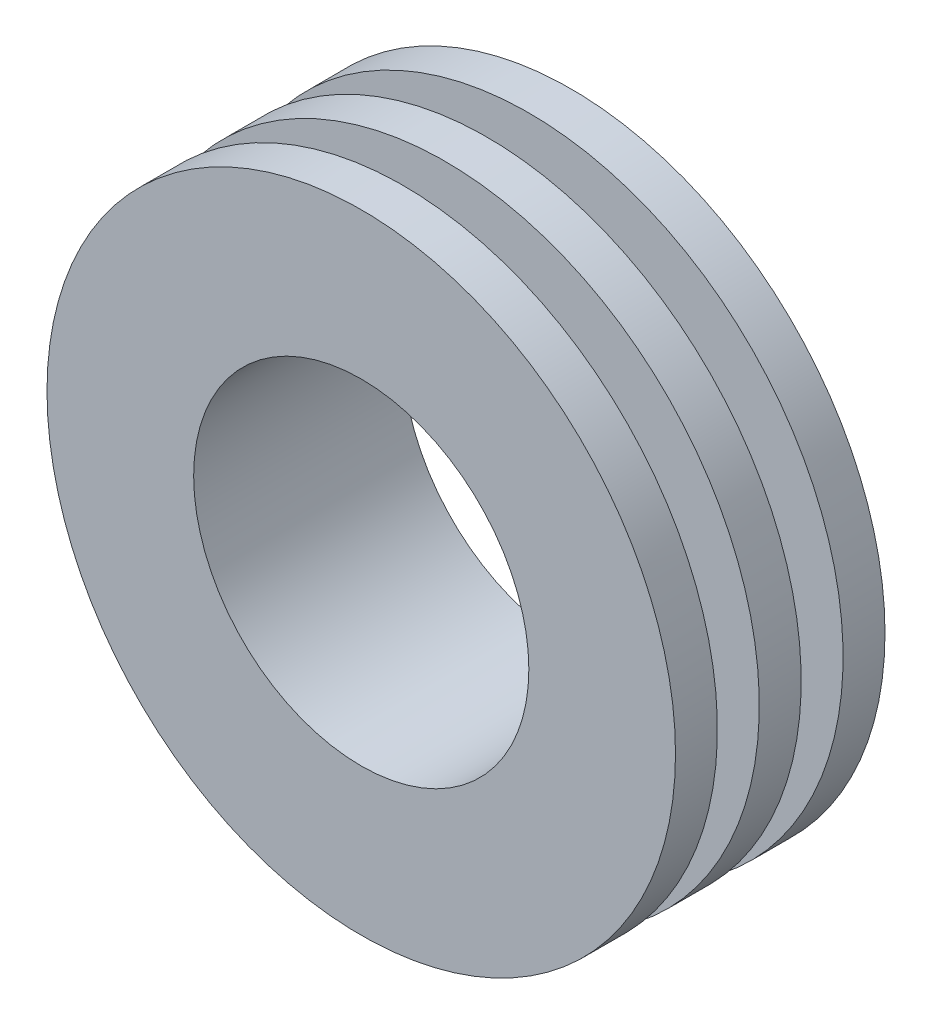
SolidWorks part; units mm, degrees
material "6061 合金"
ref_plane "前视基准面" through (0, 0, 0) normal (0, 0, 1) x (1, 0, 0)
ref_plane "上视基准面" through (0, 0, 0) normal (0, 1, 0) x (1, 0, 0)
ref_plane "右视基准面" through (0, 0, 0) normal (1, 0, 0) x (0, 0, -1)
sketch "草图1" plane through (0, 0, 0) normal (0, 0, 1) x (1, 0, 0)
  circle A0 centre (0, 0) radius 4
  circle A1 centre (0, 0) radius 7.5
  dimension "D1" = 8
  dimension "D2" = 15
extrude "凸台-拉伸1" add sketch "草图1" along normal blind 5
sketch "草图2" plane through (0, 0, 0) normal (1, 0, 0) x (0, 0, -1)
  line L0 (0, 0) -> (-5, 0) construction
  line L1 (-2.5, 0) -> (-2.5, 9.5205) construction
  line L2 (-5, 7.5) -> (-5, -7.5) construction
  line L3 (-4, 7.5) -> (-3, 7.5)
  line L4 (-4, 7.5) -> (-4, 6)
  line L5 (-4, 6) -> (-3, 6)
  line L6 (-3, 7.5) -> (-3, 6)
  line L7 (-2, 7.5) -> (-2, 6)
  line L8 (-1, 6) -> (-2, 6)
  line L9 (-1, 7.5) -> (-1, 6)
  line L10 (-1, 7.5) -> (-2, 7.5)
  dimension "D1" = 1
  dimension "D2" = 1
  dimension "D3" = 1.5
  dimension "D4" = 6
revolve "切除-旋转1" cut sketch "草图2" angle 360 about L0
